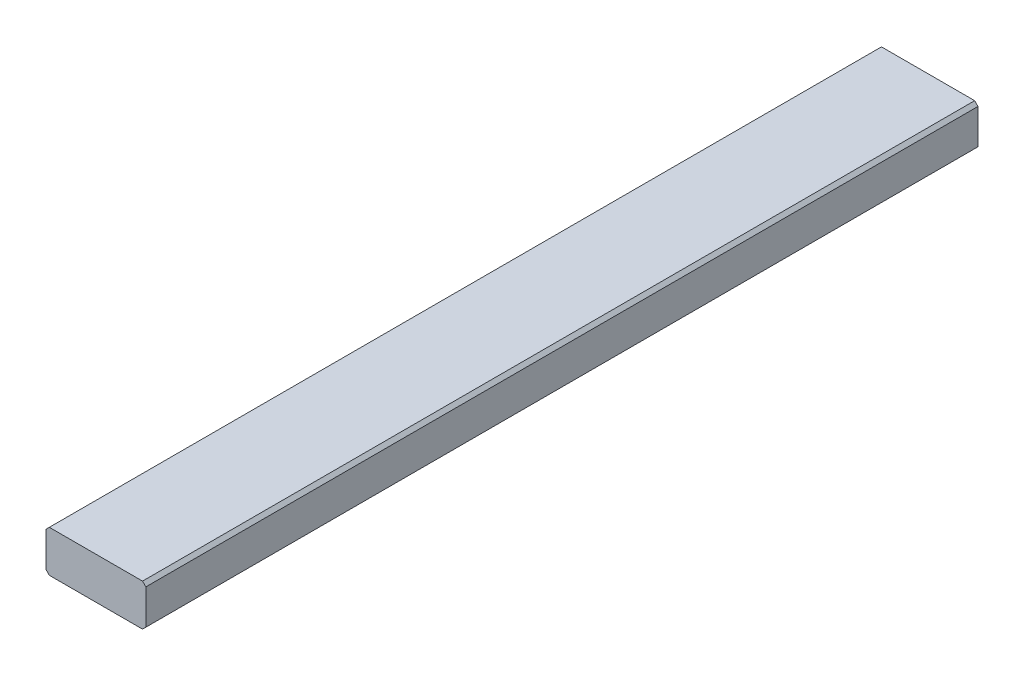
SolidWorks part; units mm, degrees
ref_plane "Спереди" through (0, 0, 0) normal (0, 0, 1) x (1, 0, 0)
ref_plane "Сверху" through (0, 0, 0) normal (0, 1, 0) x (1, 0, 0)
ref_plane "Справа" through (0, 0, 0) normal (1, 0, 0) x (0, 0, -1)
sketch "Эскиз1" plane through (0, 0, 0) normal (0, 0, 1) x (1, 0, 0)
  line L0 (-30, 10.5) -> (-28, 12.5)
  line L1 (-28, 12.5) -> (28, 12.5)
  line L2 (-30, 10.5) -> (-30, -10.5)
  line L3 (-28, -12.5) -> (28, -12.5)
  line L4 (30, 10.5) -> (30, -10.5)
  line L5 (-30, 12.5) -> (30, -12.5) construction
  line L6 (-30, -12.5) -> (30, 12.5) construction
  line L7 (-30, -10.5) -> (-28, -12.5)
  line L8 (28, -12.5) -> (30, -10.5)
  line L9 (28, 12.5) -> (30, 10.5)
  point P0 (0, 0)
  dimension "D1" = 60
  dimension "D2" = 25
extrude "Бобышка-Вытянуть1" add sketch "Эскиз1" along normal blind 500
